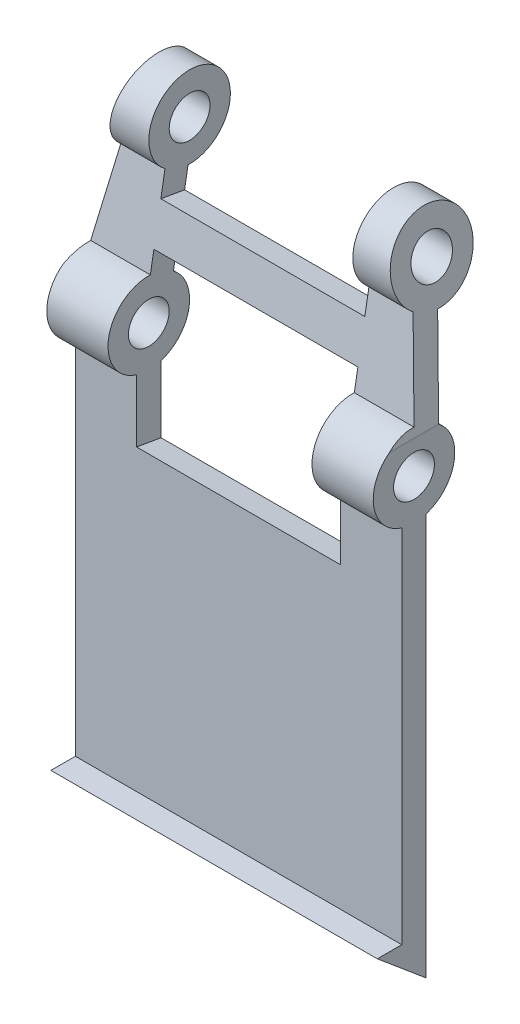
SolidWorks part; units mm, degrees
ref_plane "Front Plane" through (0, 0, 0) normal (0, 0, 1) x (1, 0, 0)
ref_plane "Top Plane" through (0, 0, 0) normal (0, 1, 0) x (1, 0, 0)
ref_plane "Right Plane" through (0, 0, 0) normal (1, 0, 0) x (0, 0, -1)
sketch "Sketch1" plane through (0, 0, 0) normal (-1, 0, 0) x (0, 1, 0)
  line L0 (3.9887, 3.0151) -> (4.9964, 0.1894) construction
  line L1 (-54.0346, 1.5) -> (-49, -4.5)
  line L2 (-49, -4.5) -> (-49, -1.5)
  line L3 (-49, -1.5) -> (-4.7697, -1.5)
  line L4 (3.9887, 3.0151) -> (14.3685, 4.8106)
  line L5 (-4.7697, 1.5) -> (-54.0346, 1.5)
  line L6 (4.9964, 0.1894) -> (15.3763, 1.9849)
  line L7 (14.3685, 4.8106) -> (15.3763, 1.9849) construction
  circle A1 centre (0, 0) radius 2.5
  arc A2 (15.3763, 1.9849) -> (14.3685, 4.8106) centre (19.3649, 5) ccw
  circle A3 centre (19.3649, 5) radius 2.5
  arc A7 (-4.7697, -1.5) -> (4.9964, 0.1894) centre (0, 0) ccw
  arc A11 (3.9887, 3.0151) -> (-4.7697, 1.5) centre (0, 0) ccw
  point P2 (19.9196, -4.1461)
  point P8 (19.9586, 1.5)
  point P23 (3.9887, 3.0151)
  point P26 (-4.7697, -1.5)
  point P29 (-4.7697, 1.5)
  dimension "D5" = 5
  dimension "D6" = 5
  dimension "D7" = 10
  dimension "D8" = 5
  dimension "D10" = 5
  dimension "D1" = 3
  dimension "D2" = 49
  dimension "D3" = 130
  dimension "D4" = 3
  dimension "D9" = 20
extrude "Boss-Extrude1" add sketch "Sketch1" along normal mid plane 40
sketch "Sketch2" plane through (0, -0.3905, -2.2575) normal (0, -0.1705, -0.9854) x (-1, 0, 0)
  line L1 (-12.5, -12.5) -> (12.5, -12.5)
  line L2 (-12.5, -12.5) -> (-12.5, 7.5)
  line L3 (-12.5, 7.5) -> (12.5, 7.5)
  line L4 (12.5, -12.5) -> (12.5, 7.5)
  dimension "D1" = 20
  dimension "D2" = 25
  dimension "D3" = 12.5
  dimension "D4" = 12.5
extrude "Cut-Extrude1" cut sketch "Sketch2" against normal through all both and the other way through all
sketch "Sketch3" plane through (0, -0.3905, -2.2575) normal (0, -0.1705, -0.9854) x (-1, 0, 0)
  line L0 (20, 24.9338) -> (-20, 24.9338) construction
  line L1 (-12.5, 24.9338) -> (12.5, 24.9338)
  line L2 (-12.5, 24.9338) -> (-12.5, 12.5)
  line L3 (-12.5, 12.5) -> (12.5, 12.5)
  line L4 (12.5, 24.9338) -> (12.5, 12.5)
  line L5 (-12.5, 4.4442) -> (-12.5, 7.5) construction
  line L6 (12.5, 7.5) -> (12.5, 4.4442) construction
  line L7 (-12.5, 7.5) -> (12.5, 7.5) construction
  dimension "D1" = 5
extrude "Cut-Extrude2" cut sketch "Sketch3" against normal through all both and the other way through all
sketch "Sketch4" plane through (0, 0, -1.5) normal (0, 0, -1) x (-1, 0, 0)
  line L0 (-20, 3.9887) -> (-16.25, 24.3649)
  line L1 (-12.5, 24.3649) -> (-20, 24.3649) construction
  line L2 (-16.25, 24.3649) -> (-20, 24.3649)
  line L3 (-20, 24.3649) -> (-20, 3.9887)
  line L4 (20, 3.9887) -> (20, 24.3649)
  line L5 (20, 24.3649) -> (12.5, 24.3649) construction
  line L6 (20, 14.3649) -> (20, 24.3649) construction
  line L7 (20, 24.3649) -> (16.25, 24.3649)
  line L8 (20, 3.9887) -> (16.25, 24.3649)
extrude "Cut-Extrude4" cut sketch "Sketch4" against normal through all both and the other way through all
